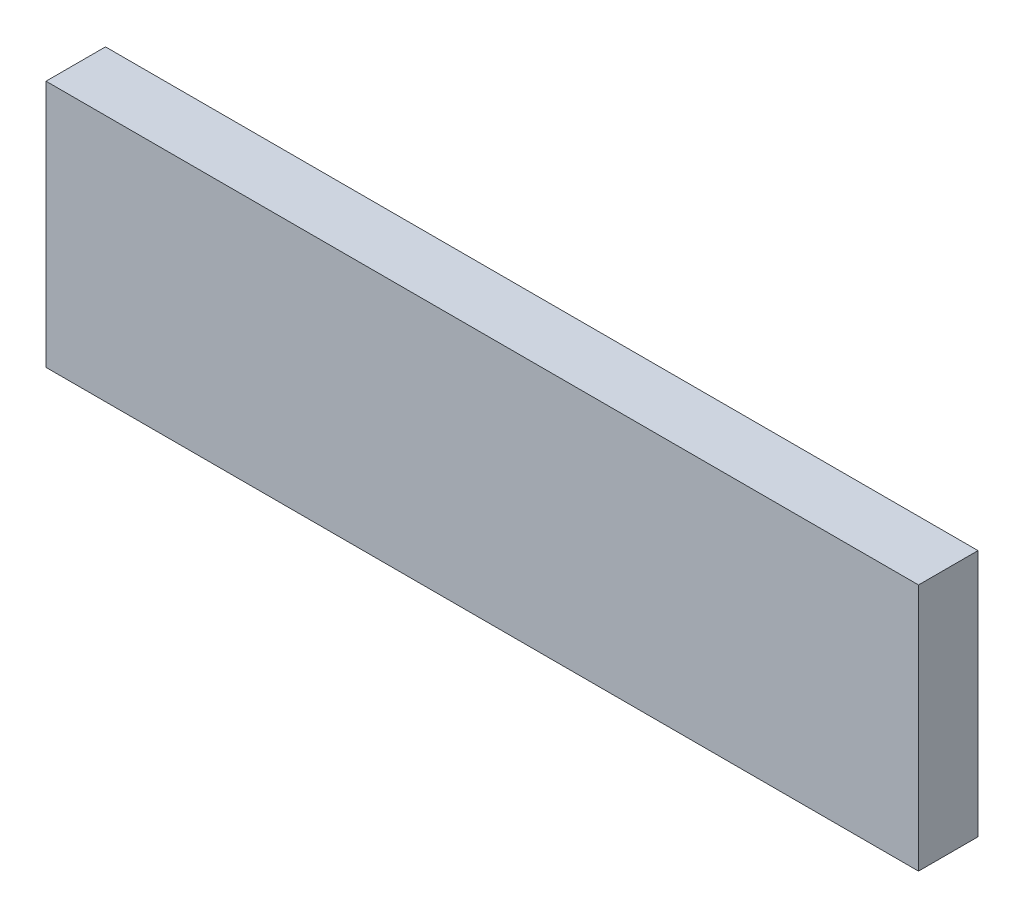
SolidWorks part; units mm, degrees
ref_plane "Front Plane" through (0, 0, 0) normal (0, 0, 1) x (1, 0, 0)
ref_plane "Top Plane" through (0, 0, 0) normal (0, 1, 0) x (1, 0, 0)
ref_plane "Right Plane" through (0, 0, 0) normal (1, 0, 0) x (0, 0, -1)
sketch "Sketch3" plane through (0, 0, 0) normal (0, 0, 1) x (1, 0, 0)
  line L1 (-44, -12.5) -> (44, -12.5)
  line L2 (-44, -12.5) -> (-44, 12.5)
  line L3 (-44, 12.5) -> (44, 12.5)
  line L4 (44, -12.5) -> (44, 12.5)
  line L5 (-44, -12.5) -> (44, 12.5) construction
  line L6 (-44, 12.5) -> (44, -12.5) construction
  point P0 (0, 0)
  dimension "D1" = 25
  dimension "D2" = 88
extrude "Boss-Extrude3" add sketch "Sketch3" along normal mid plane 6
